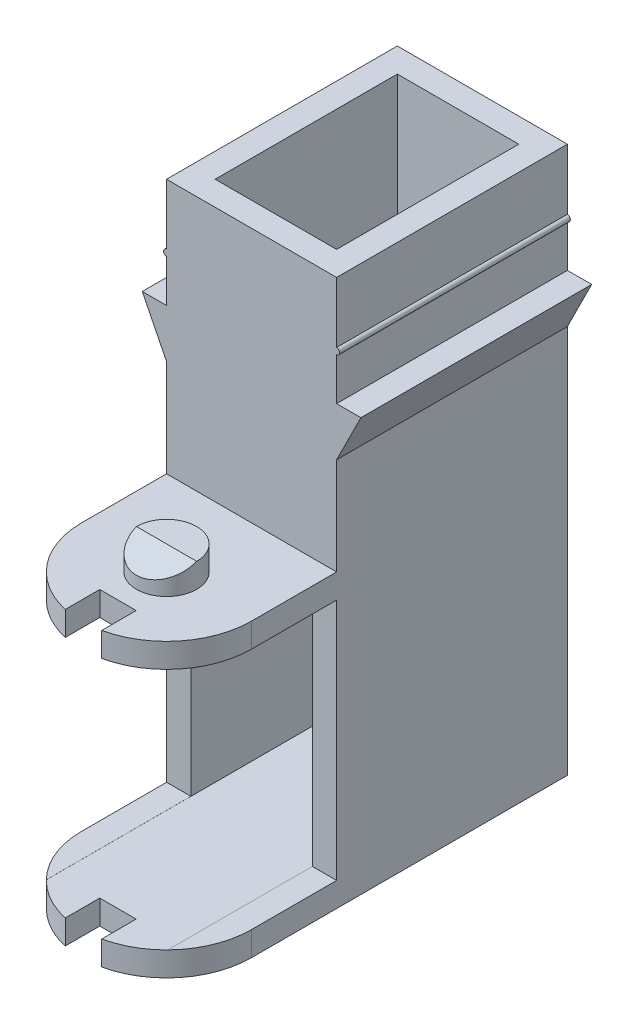
SolidWorks part; units mm, degrees
ref_plane "Front Plane" through (0, 0, 0) normal (0, 0, 1) x (1, 0, 0)
ref_plane "Top Plane" through (0, 0, 0) normal (0, 1, 0) x (1, 0, 0)
ref_plane "Right Plane" through (0, 0, 0) normal (1, 0, 0) x (0, 0, -1)
other "Configuration Table"
sketch "草图1" plane through (0, 0, 0) normal (0, 0, 1) x (1, 0, 0)
  line L0 (0, 0) -> (7, 0)
  line L1 (0, 0) -> (-7, 0)
  line L3 (-7, 0) -> (-7, -5)
  line L4 (7, 0) -> (7, -5)
  line L8 (7, -9) -> (9, -9)
  line L9 (-7, -5.5) -> (-7, -9)
  line L10 (7, -5.5) -> (7, -9)
  line L11 (-7, -9) -> (-9, -9)
  line L12 (-9, -9) -> (-7, -13)
  line L13 (9, -9) -> (7, -13)
  line L20 (0, -45) -> (7, -45)
  line L22 (7, -45) -> (7, -13)
  line L23 (0, -45) -> (-7, -45)
  line L24 (-7, -45) -> (-7, -13)
  arc A0 (7, -5) -> (7, -5.5) centre (7, -5.25) cw
  arc A1 (-7, -5) -> (-7, -5.5) centre (-7, -5.25) ccw
extrude "凸台-拉伸1" add sketch "草图1" along normal blind 19 contours L23 L24 L12 L11 L9 A1 L3 L1 L0 L4 A0 L10 L8 L13 L22 L20
sketch "草图2" plane through (0, 0, 0) normal (0, 1, 0) x (1, 0, 0)
  line L7 (0, -2) -> (5, -2)
  line L8 (5, -2) -> (5, -9.5)
  line L9 (5, -9.5) -> (5, -17)
  line L10 (5, -17) -> (0, -17)
  line L11 (0, -17) -> (-5, -17)
  line L12 (-5, -17) -> (-5, -9.5)
  line L13 (-5, -9.5) -> (-5, -2)
  line L14 (-5, -2) -> (0, -2)
extrude "切除-拉伸2" cut sketch "草图2" against normal blind 43
sketch "草图3" plane through (0, 0, 19) normal (0, 0, 1) x (1, 0, 0)
  line L0 (0, -23) -> (5, -23)
  line L3 (0, -43) -> (5, -43)
  line L9 (0, -23) -> (-5, -23)
  line L10 (-5, -23) -> (-5, -43)
  line L11 (-5, -43) -> (0, -43)
  line L13 (5, -43) -> (5, -23)
extrude "切除-拉伸3" cut sketch "草图3" against normal blind 2 contours L3 L13 L0 L9 L10 L11
sketch "草图4" plane through (0, 0, 19) normal (0, 0, 1) x (1, 0, 0)
  line L0 (7, -45) -> (7, -13) construction
  line L1 (-7, -45) -> (7, -45)
  line L2 (-7, -45) -> (-7, -42.9962)
  line L3 (-7, -42.9962) -> (7, -42.9962)
  line L4 (7, -45) -> (7, -42.9962)
  line L5 (5, -23) -> (7, -23)
  line L6 (7, -23) -> (7, -21)
  line L7 (7, -21) -> (-7, -21)
  line L8 (-7, -45) -> (-7, -13) construction
  line L9 (-7, -21) -> (-7, -23)
  line L10 (-7, -23) -> (5, -23)
  line M6 (5, -43) -> (-5, -43)
  line M7 (-5, -43) -> (-5, -23)
  line M9 (5, -23) -> (5, -43)
  line M10 (-7, -45) -> (7, -45)
  line M11 (7, -45) -> (7, -13)
  line M23 (-7, -13) -> (-7, -45)
extrude "凸台-拉伸2" add sketch "草图4" along normal blind 14 contours L3 M23 M10 M11 M9 M6 M7 | L10 L5 L6 L7 L9
sketch "草图5" plane through (0, -45, 0) normal (0, -1, 0) x (1, 0, 0)
  line L0 (0, 33) -> (0, 26)
  line L1 (-7, 33) -> (7, 33) construction
  circle A0 centre (0, 26) radius 2.48
extrude "凸台-拉伸3" add sketch "草图5" along normal blind 2 contours A0
sketch "草图6" plane through (0, -45, 0) normal (0, -1, 0) x (-1, 0, 0)
  line L0 (7, -33) -> (7, 0) construction
  line L1 (-7, -33) -> (-7, 0) construction
  line L2 (7, -26) -> (7, -33)
  line L3 (7, -33) -> (0, -33)
  line L4 (0, -33) -> (-7, -33)
  line L5 (-7, -33) -> (-7, -26)
  arc A0 (7, -26) -> (-7, -26) centre (0, -26) cw
  line M3 (-7, 0) -> (-7, -33)
  line M4 (-7, -33) -> (7, -33)
  line M5 (7, -33) -> (7, 0)
extrude "切除-拉伸4" cut sketch "草图6" against normal blind 50 contours A0 M5 M4 | A0 M4 M3
sketch "草图7" plane through (0, -21, 0) normal (0, 1, 0) x (1, 0, 0)
  circle A0 centre (0, -26) radius 2.48
extrude "凸台-拉伸4" add sketch "草图7" along normal blind 2 contours A0
sketch "草图8" plane through (0, -21, 0) normal (0, 1, 0) x (1, 0, 0)
  line L0 (3.5429, -28.48) -> (4.9142, -28.48)
  line L1 (4.9142, -26) -> (4.9142, -28.48)
  line L2 (3.5429, -26) -> (4.9142, -26)
  line L3 (3.5429, -28.48) -> (3.5429, -26)
extrude "凸台-拉伸5" add sketch "草图8" along normal blind 2 contours L2 L1 L0 L3
sketch "草图9" plane through (4.9142, 0, 0) normal (1, 0, 0) x (0, 0, -1)
  line L0 (-26, -19) -> (-28.48, -19)
  line L1 (-28.48, -19) -> (-28.48, -20)
  line L2 (-28.48, -19) -> (-28.48, -21) construction
  line L3 (-28.48, -20) -> (-26, -19)
extrude "切除-拉伸5" cut sketch "草图9" against normal blind 10 contours L3 L0 L1
sketch "草图10" plane through (4.9142, 0, 0) normal (1, 0, 0) x (0, 0, -1)
  line L0 (-26, -19) -> (-26, -21)
  line L1 (-26, -21) -> (-28.48, -21)
  line L2 (-28.48, -21) -> (-28.48, -20)
  line L3 (-28.48, -20) -> (-26, -19)
extrude "切除-拉伸6" cut sketch "草图10" against normal blind 2 contours L3 L0 L1 L2
sketch "草图11" plane through (0, -47, 0) normal (0, -1, 0) x (-1, 0, 0)
  line L1 (-5.2385, -26.0118) -> (-5.2385, -28.4918)
  line L2 (-5.2385, -28.4918) -> (-3.1538, -28.4918)
  line L3 (-3.1538, -28.4918) -> (-3.1538, -26.0118)
  line L4 (-3.1538, -26.0118) -> (-5.2385, -26.0118)
extrude "凸台-拉伸7" add sketch "草图11" against normal blind 2 contours L1 L2 L3 L4
sketch "草图12" plane through (5.2385, 0, 0) normal (1, 0, 0) x (0, 0, -1)
  line L0 (-28.4918, -47) -> (-28.4918, -46)
  line L1 (-28.4918, -45) -> (-28.4918, -47) construction
  line L2 (-28.4918, -46) -> (-26.0118, -47)
  line L3 (-26.0118, -47) -> (-28.4918, -47)
extrude "切除-拉伸7" cut sketch "草图12" against normal blind 20 contours L3 L0 L2
sketch "草图13" plane through (5.2385, 0, 0) normal (1, 0, 0) x (0, 0, -1)
  line L0 (-28.4918, -46) -> (-26.0118, -47)
  line L1 (-26.0118, -47) -> (-26, -45)
  line L2 (-28.48, -45) -> (-23.52, -45) construction
  line L3 (-26, -45) -> (-28.4918, -45)
  line L4 (-28.4918, -45) -> (-28.4918, -46)
extrude "切除-拉伸8" cut sketch "草图13" against normal blind 2.5 contours L4 L0 L1 L3
sketch "草图14" plane through (0, -45, 0) normal (0, -1, 0) x (1, 0, 0)
  line L0 (0, 33) -> (0, 30)
  line L1 (0, 30) -> (1.5, 30)
  line L2 (0, 30) -> (-1.5, 30)
  line L3 (-1.5, 30) -> (-1.5, 32.8374)
  line L4 (1.5, 30) -> (1.5, 33.1754)
  line L5 (1.5, 33.1754) -> (-1.5, 33.1754)
  line L6 (-1.5, 33.1754) -> (-1.5, 32.8374)
  arc A0 (7, 26) -> (-7, 26) centre (0, 26) ccw construction
  arc M10 (7, 26) -> (-7, 26) centre (0, 26) ccw
extrude "切除-拉伸9" cut sketch "草图14" against normal blind 50 contours L1 L4 L0 M10 | L3 L2 L0 M10 | L5 L6 L4 M10
